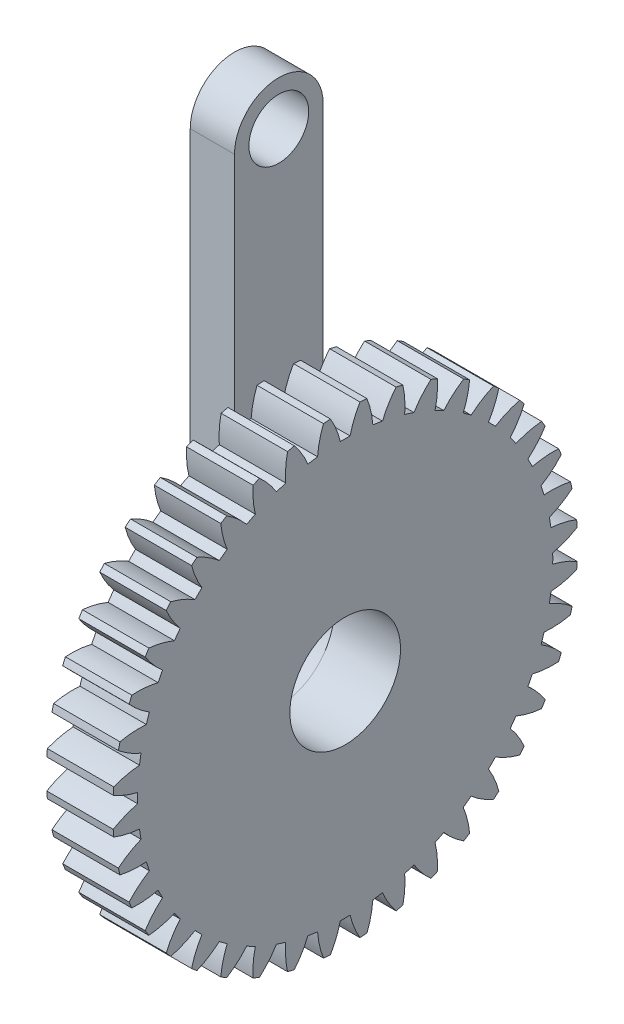
SolidWorks part; units mm, degrees
ref_plane "Plane1" through (0, 0, 0) normal (0, 0, 1) x (1, 0, 0)
ref_plane "Plane2" through (0, 0, 0) normal (0, 1, 0) x (1, 0, 0)
ref_plane "Plane3" through (0, 0, 0) normal (1, 0, 0) x (0, 0, -1)
sketch "HoldingSke" plane through (0, 0, 0) normal (0, 1, 0) x (1, 0, 0)
  line L0 (0, 0) -> (0.383, -0.3214)
  line L1 (-15, 0) -> (100, 0) construction
  line L2 (0, 0) -> (-2.1039, 2.3779)
  line L3 (0, 0) -> (-11.863, 4.5341)
  line L4 (0, 0) -> (6.6156, 5.5511)
  line L5 (0, 0) -> (-46.8476, -17.4728)
  line L6 (0, 0) -> (-9.9476, -6.7116)
  line L7 (-2.1039, 2.3779) -> (8.6586, 51.2059)
  line L8 (-76.2, 54.61) -> (-76.1, 54.61)
  line L9 (-71.009, 38.7566) -> (-53.1078, 45.2721)
  line L10 (-76.2, 71.12) -> (104.1128, 71.12)
  line L11 (0, 0) -> (-12, 0)
  line L12 (-76.2, 101.6) -> (-76.133, 101.6)
  line L13 (24.9733, 27.94) -> (52.9518, 28.4284)
  line L14 (24.9733, 27.94) -> (24.9743, 27.94)
  line L15 (24.9733, 27.94) -> (100.4006, 29.5858)
  line L16 (-63.627, -2) -> (-12.827, -2)
  circle A0 centre (0, 0) radius 0.4
  circle A1 centre (0, 0) radius 37.499
  circle A2 centre (0, 0) radius 37.5
  circle A3 centre (0, 0) radius 0.4
  dimension "MHD" = 74.998
  dimension "Hub_dia" = 75
  dimension "Bore" = 0.8
  dimension "MBD" = 0.8
  dimension "Num_teeth" = 40
  dimension "Pitch" = 0.5
  dimension "Overall_len" = 50
  dimension "Show_teeth" = 40
  dimension "Thickness" = 12
  dimension "OAL" = 50.0001
  dimension "T_dim" = 0.1
  dimension "Ap" = 20
  dimension "H" = 19.05
  dimension "Pitch_radius" = 180.3128
  dimension "Width" = 12
  dimension "Backlash" = 0.067
  dimension "Addendum_fac" = 1
  dimension "Dedendum_fac" = 1.25
  dimension "Clearance_fac" = 0.25
  dimension "Dedendum_add" = 0.001
  dimension "Module" = 2
sketch "BasProSke" plane through (0, 0, 0) normal (0, 1, 0) x (1, 0, 0)
  line L0 (-10, 0) -> (60, 0) construction
  line L1 (0, 0) -> (0, 42)
  line L2 (0, 0) -> (12, 0)
  line L3 (12, 0) -> (12, 42)
  line L4 (12, 42) -> (0, 42)
  dimension "Thickness" = 12
  dimension "Diameter" = 84
revolve "Base-Revolve" add sketch "BasProSke" angle 360 about L0
sketch "TooCutSke" plane through (0, 0, 0) normal (1, 0, 0) x (0, 0, -1)
  line L1 (0, 0) -> (0, 107) construction
  line L2 (0, 0) -> (-1.6876, 39.9644) construction
  line L3 (0, 0) -> (-6.2726, 79.7007) construction
  line L4 (-1.6876, 39.9644) -> (-3.1363, 39.8504) construction
  arc A0 (0.8828, 37.4886) -> (-0.8828, 37.4886) centre (0, 0) ccw
  arc A1 (2.6784, 41.94) -> (-2.6784, 41.94) centre (0, 0) ccw
  circle A2 centre (0, 0) radius 40 construction
  circle A3 centre (0, 0) radius 37.5877 construction
  arc A4 (-0.8828, 37.4886) -> (-2.6784, 41.94) centre (-16.451, 33.7965) ccw
  arc A5 (2.6784, 41.94) -> (0.8828, 37.4886) centre (16.451, 33.7965) ccw
  dimension "Root_dia" = 74.998
  dimension "Overcut_dia" = 84.0508
  dimension "Pitch_dia" = 80
  dimension "Base_dia" = 75.1754
  dimension "Flank_rad" = 16
  dimension "Half_ang" = 4.5
  dimension "Half_CT" = 1.4531
extrude "ToothCut" cut sketch "TooCutSke" along normal through all
fillet "Breaks" [suppressed] radius 0.04
fillet "RootFillets" [suppressed] radius 0.501
pattern_circular "TeethCuts" count 40 every 9 about axis through (-10, 0, 0) along (1, 0, 0) of "ToothCut", "RootFillets", "Breaks"
sketch "HubNeaOneSke" plane through (0, 0, 0) normal (-1, 0, 0) x (0, 0, 1)
  circle A0 centre (0, 0) radius 37.499
  dimension "Diameter" = 74.998
extrude "HubNearOne" [suppressed] add sketch "HubNeaOneSke" along normal blind 38.0001
sketch "HubNeaBotSke" plane through (0, 0, 0) normal (-1, 0, 0) x (0, 0, 1)
  circle A0 centre (0, 0) radius 37.499
  dimension "Diameter" = 74.998
extrude "HubNearBoth" [suppressed] add sketch "HubNeaBotSke" along normal blind 19
ref_plane "FarPln" through (12, 0, 0) normal (1, 0, 0) x (0, 0, -1)
sketch "HubFarSke" plane through (12, 0, 0) normal (1, 0, 0) x (0, 0, -1)
  circle A0 centre (0, 0) radius 37.499
  dimension "Diameter" = 74.998
extrude "HubFar" [suppressed] add sketch "HubFarSke" along normal blind 19
sketch "BorSke" plane through (0, 0, 0) normal (1, 0, 0) x (0, 0, -1)
  circle A0 centre (0, 0) radius 0.4
  dimension "Diameter" = 0.8
extrude "Bore" cut sketch "BorSke" along normal mid plane 100.0001
sketch "KeySke" plane through (0, 0, 0) normal (1, 0, 0) x (0, 0, -1)
  line L0 (-0.05, 0) -> (-0.05, 0.5)
  line L1 (-0.05, 0.5) -> (0.05, 0.5)
  line L2 (0.05, 0.5) -> (0.05, 0)
  line L3 (0, 0) -> (0, 34) construction
  line L4 (-0.05, 0) -> (0.05, 0)
  dimension "Offset" = 0.5
  dimension "Width" = 0.1
extrude "Keyway" [suppressed] cut sketch "KeySke" along normal mid plane 100.0001
pattern_circular "Keyway2" [suppressed] count 2 every 90 about axis through (-10, 0, 0) along (1, 0, 0)
scale "Scale1" scale about centroid uniform scaling yes scale factor 0.5
sketch "Sketch1" plane through (9, 0, 0) normal (1, 0, 0) x (0, 0, -1)
  circle A0 centre (0, -0.2) radius 5
  circle A1 centre (0, 0) radius 0.2 construction
  dimension "D1" = 10
extrude "Cut-Extrude1" cut sketch "Sketch1" against normal through all
sketch "Sketch2" plane through (3, 0, 0) normal (-1, 0, 0) x (0, 0, 1)
  line L2 (-4, 40) -> (-4, 6.6521)
  line L3 (4, 40) -> (4, 6.6521)
  arc A1 (-4, 6.6521) -> (4, 6.6521) centre (0, 0) ccw
  arc A2 (4, 40) -> (-4, 40) centre (0, 40) ccw
  circle A4 centre (0, 0) radius 5.2
  circle A5 centre (0, 40) radius 2.7
  dimension "D2" = 8
extrude "Boss-Extrude1" add sketch "Sketch2" along normal blind 4
equation "' \"Module@HoldingSke\" = 6.35"
equation "' \"Num_teeth@HoldingSke\" = 12"
equation "' \"Ap@HoldingSke\" =  20"
equation "' \"Ap@HoldingSke\" = 20"
equation "' \"Width@HoldingSke\" = 0.5 * 25.4"
equation "' \"Hub_dia@HoldingSke\"= 1 * 25.4"
equation "' \"Hub_dia@HoldingSke\" = 1 * 25.4"
equation "' \"Overall_len@HoldingSke\" = 1.0 * 25.4"
equation "' \"Bore@HoldingSke\" = 0.75 * 25.4"
equation "' \"T_dim@HoldingSke\" = 0.1 * 25.4"
equation "' \"Width@KeySke\" = 0.25 * 25.4"
equation "' \"Show_teeth@HoldingSke\" = 13"
equation "' \"Backlash@HoldingSke\" = 0.009 * 25.4"
equation "' \"Addendum_fac@HoldingSke\" = 1.0"
equation "' \"Dedendum_fac@HoldingSke\" = 1.25"
equation "' \"Dedendum_add@HoldingSke\" = 0.00005 * 25.4"
equation "' \"Clearance_fac@HoldingSke\" = 0.25"
equation "\"Pitch@HoldingSke\" = 1 / \"Module@HoldingSke\""
equation "\"Overcut_dia@TooCutSke\" = (\"Num_teeth@HoldingSke\" + 2 * \"Addendum_fac@HoldingSke\") / \"Pitch@HoldingSke\" + 0.002 * 25.4"
equation "\"Pitch_dia@TooCutSke\" = \"Num_teeth@HoldingSke\" / \"Pitch@HoldingSke\""
equation "\"Base_dia@TooCutSke\" = \"Num_teeth@HoldingSke\" / \"Pitch@HoldingSke\" * cos((\"Ap@HoldingSke\"  * 3.14159265 / 180))"
equation "\"Root_dia@TooCutSke\" = (\"Num_teeth@HoldingSke\" + 2) / \"Pitch@HoldingSke\" - 2 * (\"Addendum_fac@HoldingSke\" + \"Dedendum_fac@HoldingSke\") / \"Pitch@HoldingSke\" - \"Dedendum_add@HoldingSke\" * 2"
equation "\"Half_ang@TooCutSke\" = 180 / \"Num_teeth@HoldingSke\""
equation "\"Half_CT@TooCutSke\" = \"Num_teeth@HoldingSke\" / \"Pitch@HoldingSke\" * sin((3.14159265 / 2 / \"Num_teeth@HoldingSke\")) / 2 - 7 * \"Backlash@HoldingSke\" / 4"
equation "\"Flank_rad@TooCutSke\" = \"Num_teeth@HoldingSke\" / \"Pitch@HoldingSke\" / 5"
equation "\"Radius@RootFillets\" = \"Clearance_fac@HoldingSke\" / \"Pitch@HoldingSke\" + \"Dedendum_add@HoldingSke\""
equation "\"Break_rad@Breaks\" = 0.02 / \"Pitch@HoldingSke\""
equation "\"Thickness@HoldingSke\" = \"Width@HoldingSke\""
equation "\"OAL@HoldingSke\" = \"Thickness@HoldingSke\""
equation "\"MHD@HoldingSke\" = (\"Num_teeth@HoldingSke\" + 2) / \"Pitch@HoldingSke\" - 2 * (\"Addendum_fac@HoldingSke\" + \"Dedendum_fac@HoldingSke\")  / \"Pitch@HoldingSke\" - \"Dedendum_add@HoldingSke\" * 2"
equation "\"MBD@HoldingSke\" = (\"Num_teeth@HoldingSke\" + 2) / \"Pitch@HoldingSke\" - 2 * (\"Addendum_fac@HoldingSke\" + \"Dedendum_fac@HoldingSke\")  / \"Pitch@HoldingSke\" - \"Dedendum_add@HoldingSke\" * 2 - 0.002 * 25.4"
equation "\"MHD@HoldingSke\" = ((sgn( \"MHD@HoldingSke\" - \"Hub_dia@HoldingSke\" )-1)*( \"MHD@HoldingSke\" - \"Hub_dia@HoldingSke\" ))/-2+ \"Hub_dia@HoldingSke\""
equation "\"MBD@HoldingSke\" = ((sgn( \"MBD@HoldingSke\" - \"Bore@HoldingSke\" )-1)*( \"MBD@HoldingSke\" - \"Bore@HoldingSke\" ))/-2+ \"Bore@HoldingSke\""
equation "\"OAL@HoldingSke\" = ((sgn( \"OAL@HoldingSke\" - \"Overall_len@HoldingSke\" )+1)*( \"OAL@HoldingSke\" - \"Overall_len@HoldingSke\" ))/2 + \"Overall_len@HoldingSke\" + 0.000002 * 25.4"
equation "\"Num_teeth@TeethCuts\" = int( \"Show_teeth@HoldingSke\" ) + 1"
equation "\"Num_teeth@TeethCuts\" = ((sgn( \"Num_teeth@TeethCuts\" - \"Num_teeth@HoldingSke\" )-1)*( \"Num_teeth@TeethCuts\" - \"Num_teeth@HoldingSke\" ))/-2+ \"Num_teeth@HoldingSke\""
equation "\"Num_teeth@TeethCuts\" = ((sgn( \"Num_teeth@TeethCuts\" - 2.0)+1)*( \"Num_teeth@TeethCuts\" - 2.0))/2 +2.0"
equation "\"Angle@TeethCuts\" = 360.0 / \"Num_teeth@HoldingSke\""
equation "\"Diameter@BasProSke\" = (\"Num_teeth@HoldingSke\" + 2 * \"Addendum_fac@HoldingSke\") / \"Pitch@HoldingSke\""
equation "\"Thickness@BasProSke\"  = \"Thickness@HoldingSke\""
equation "' \"Fillet_rad@BasProSke\" =  \"Thickness@HoldingSke\" * 0.05"
equation "' \"Fillet_rad@BasProSke\" = \"Thickness@HoldingSke\" * 0.05"
equation "\"MHD@HoldingSke\" = ((sgn( \"MHD@HoldingSke\" - \"Root_dia@TooCutSke\" )-1)*( \"MHD@HoldingSke\" - \"Root_dia@TooCutSke\" ))/-2+ \"Root_dia@TooCutSke\""
equation "\"Diameter@HubNeaOneSke\" = \"MHD@HoldingSke\""
equation "\"Length@HubNearOne\" = \"OAL@HoldingSke\" - \"Thickness@BasProSke\""
equation "\"Diameter@HubNeaBotSke\" = \"MHD@HoldingSke\""
equation "\"Length@HubNearBoth\" = ( \"OAL@HoldingSke\" - \"Thickness@BasProSke\" ) / 2.0"
equation "\"Thickness@FarPln\" = \"Thickness@BasProSke\""
equation "\"Diameter@HubFarSke\" = \"MHD@HoldingSke\""
equation "\"Length@HubFar\" = ( \"OAL@HoldingSke\" - \"Thickness@BasProSke\" ) / 2.0"
equation "\"Diameter@BorSke\" = \"MBD@HoldingSke\""
equation "\"D1@Bore\" = \"OAL@HoldingSke\" * 2.0"
equation "\"D1@Keyway\" = \"OAL@HoldingSke\" * 2.0"
equation "\"Offset@KeySke\" = \"T_dim@HoldingSke\" + \"MBD@HoldingSke\" / 2.0"
